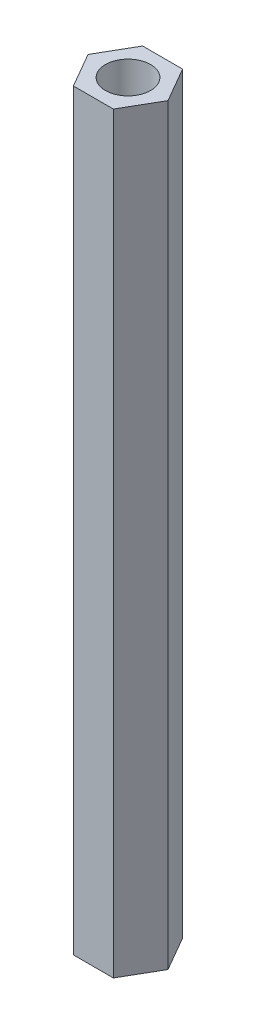
SolidWorks part; units mm, degrees
material "Brass"
ref_plane "Front Plane" through (0, 0, 0) normal (0, 0, 1) x (1, 0, 0)
ref_plane "Top Plane" through (0, 0, 0) normal (0, 1, 0) x (1, 0, 0)
ref_plane "Right Plane" through (0, 0, 0) normal (1, 0, 0) x (0, 0, -1)
sketch "Sketch1" plane through (0, 0, 0) normal (0, 1, 0) x (1, 0, 0)
  line L1 (2.6558, 0) -> (1.3279, 2.3)
  line L2 (1.3279, 2.3) -> (-1.3279, 2.3)
  line L3 (-1.3279, 2.3) -> (-2.6558, 0)
  line L4 (-2.6558, 0) -> (-1.3279, -2.3)
  line L5 (-1.3279, -2.3) -> (1.3279, -2.3)
  line L6 (1.3279, -2.3) -> (2.6558, 0)
  circle A0 centre (0, 0) radius 2.3 construction
  point P1 (-1.9919, -1.15)
  point P10 (1.9919, 1.15)
  dimension "D1" = 4.6
extrude "Boss-Extrude1" add sketch "Sketch1" along normal mid plane 50
sketch "Sketch2" plane through (0, 25, 0) normal (0, 1, 0) x (1, 0, 0)
  circle A0 centre (0, 0) radius 1.5
extrude "Cut-Extrude1" cut sketch "Sketch2" against normal blind 8
sketch "Sketch3" plane through (0, -25, 0) normal (0, -1, 0) x (1, 0, 0)
  circle A0 centre (0, 0) radius 1.5
extrude "Cut-Extrude2" cut sketch "Sketch3" against normal blind 8
